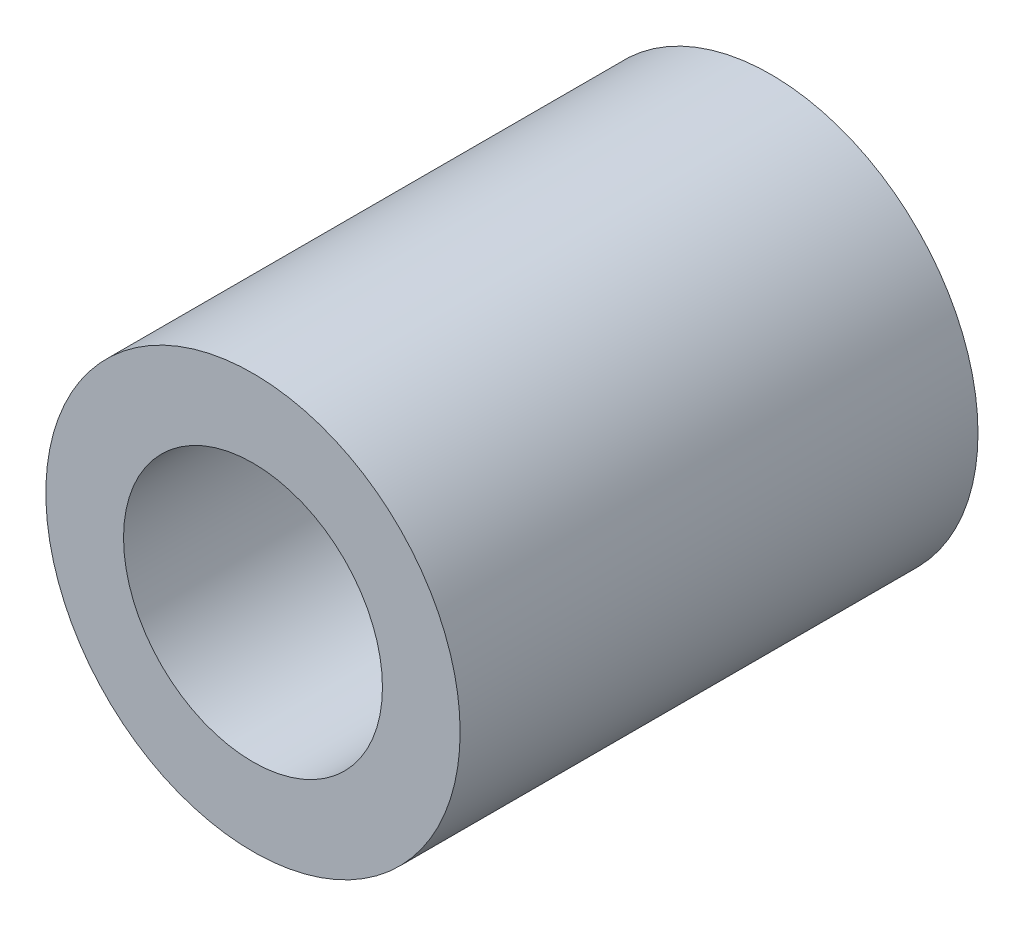
SolidWorks part; units mm, degrees
ref_plane "Front Plane" through (0, 0, 0) normal (0, 0, 1) x (1, 0, 0)
ref_plane "Top Plane" through (0, 0, 0) normal (0, 1, 0) x (1, 0, 0)
ref_plane "Right Plane" through (0, 0, 0) normal (1, 0, 0) x (0, 0, -1)
sketch "Sketch1" plane through (0, 0, 0) normal (0, 0, 1) x (1, 0, 0)
  circle A0 centre (0, 0) radius 4
  circle A1 centre (0, 0) radius 2.5
  dimension "D1" = 8
  dimension "D2" = 5
extrude "Boss-Extrude1" add sketch "Sketch1" along normal blind 10
